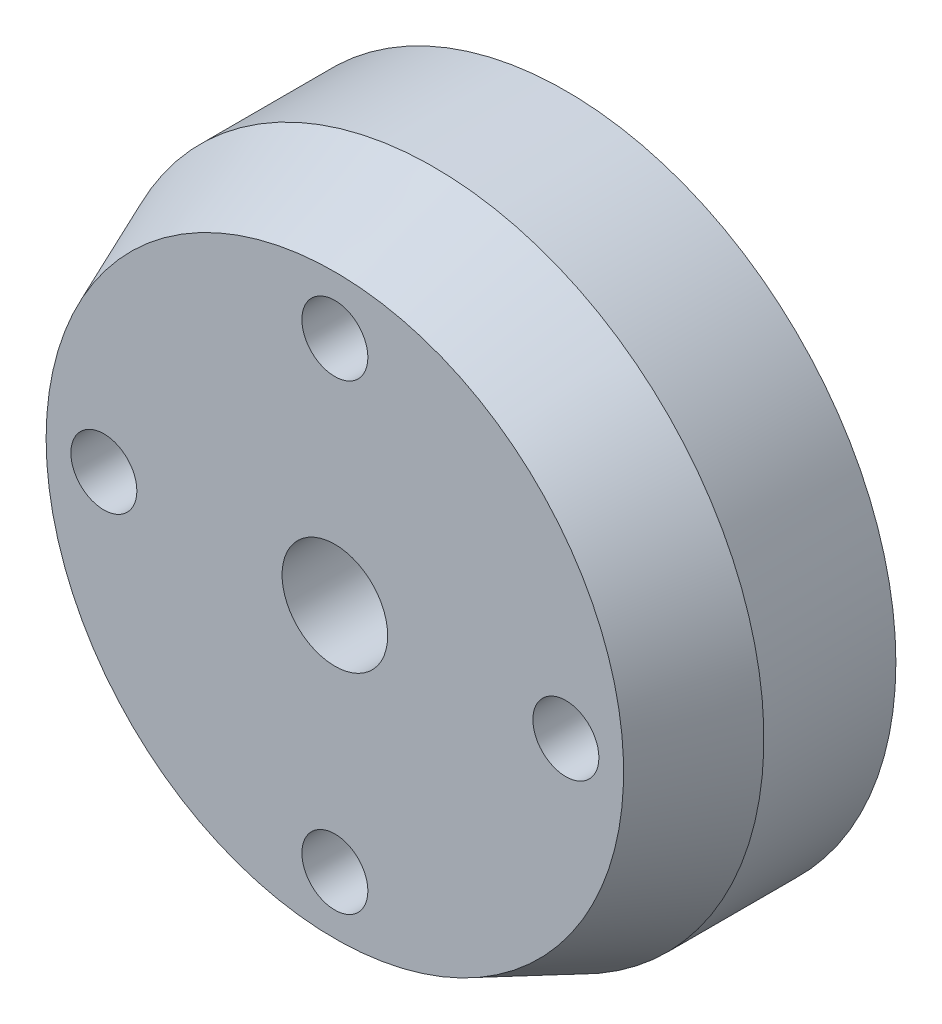
SolidWorks part; units mm, degrees
ref_plane "Front Plane" through (0, 0, 0) normal (0, 0, 1) x (1, 0, 0)
ref_plane "Top Plane" through (0, 0, 0) normal (0, 1, 0) x (1, 0, 0)
ref_plane "Right Plane" through (0, 0, 0) normal (1, 0, 0) x (0, 0, -1)
sketch "Sketch1" plane through (0, 0, 0) normal (0, 0, 1) x (1, 0, 0)
  circle A0 centre (0, 0) radius 10
  circle A1 centre (0, 0) radius 1.6
  dimension "D1" = 20
  dimension "D2" = 3.2
extrude "Boss-Extrude1" add sketch "Sketch1" along normal blind 7
sketch "Sketch2" plane through (0, 0, 7) normal (0, 0, 1) x (1, 0, 0)
  line L0 (0, 0) -> (7, 0) construction
  circle A0 centre (7, 0) radius 1
  circle A1 centre (0, -7) radius 1
  circle A2 centre (-7, 0) radius 1
  circle A3 centre (0, 7) radius 1
  point P13 (0, 0)
  dimension "D1" = 2
  dimension "D2" = 7
  dimension "D3" = 4
extrude "Cut-Extrude1" cut sketch "Sketch2" against normal blind 7
chamfer "Chamfer2" distance 3 distance2 1.25 1 edges at (10, 0, 7)
